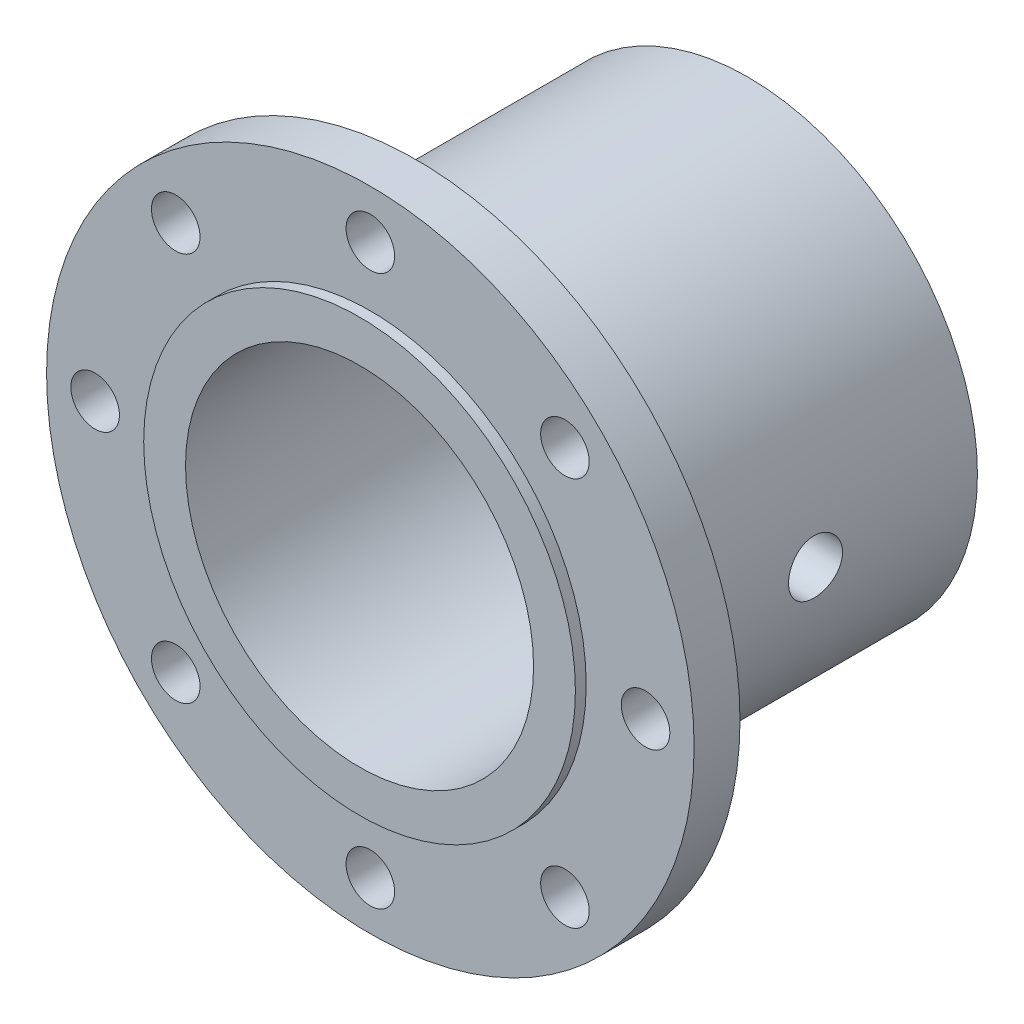
SolidWorks part; units mm, degrees
material "ASTM A36 Steel"
ref_plane "Front Plane" through (0, 0, 0) normal (0, 0, 1) x (1, 0, 0)
ref_plane "Top Plane" through (0, 0, 0) normal (0, 1, 0) x (1, 0, 0)
ref_plane "Right Plane" through (0, 0, 0) normal (1, 0, 0) x (0, 0, -1)
sketch "Sketch1" plane through (0, 0, 0) normal (1, 0, 0) x (0, 0, -1)
  line L0 (-9.5025, 5.665) -> (-81.5025, 5.665)
  line L1 (-81.5025, 5.665) -> (-81.5025, 13.415)
  line L2 (-81.5025, 13.415) -> (-79.5025, 13.415)
  line L3 (-79.5025, 13.415) -> (-79.5025, 33.415)
  line L4 (-79.5025, 33.415) -> (-71.0025, 33.415)
  line L5 (-71.0025, 33.415) -> (-71.0025, 15.915)
  line L6 (-71.0025, 15.915) -> (-9.5025, 15.915)
  line L7 (-9.5025, 15.915) -> (-9.5025, 5.665)
  line L8 (-81.5025, -26.585) -> (-9.5025, -26.585)
  dimension "D1" = 72
  dimension "D2" = 2
  dimension "D3" = 8.5
  dimension "D4" = 32.25
  dimension "D5" = 42.5
  dimension "D6" = 60
  dimension "D7" = 40
revolve "Revolve1" add sketch "Sketch1" angle 360 about L8
sketch "Sketch2" plane through (0, 0, 79.5025) normal (0, 0, 1) x (1, 0, 0)
  circle A1 centre (51, -26.585) radius 4.5
  dimension "D2" = 9
extrude "Cut-Extrude1" cut sketch "Sketch2" against normal through all both and the other way through all
pattern_circular "CirPattern1" count 8 every 45 about axis through (0, -26.585, 0) along (0, 0, 1) of "Cut-Extrude1"
sketch "Sketch3" plane through (0, 0, 0) normal (1, 0, 0) x (0, 0, -1)
  line L0 (-9.5025, -69.085) -> (-9.5025, 15.915) construction
  circle A0 centre (-39.5025, -26.585) radius 5
  dimension "D1" = 10
  dimension "D2" = 30
extrude "Cut-Extrude2" cut sketch "Sketch3" along normal blind 70
